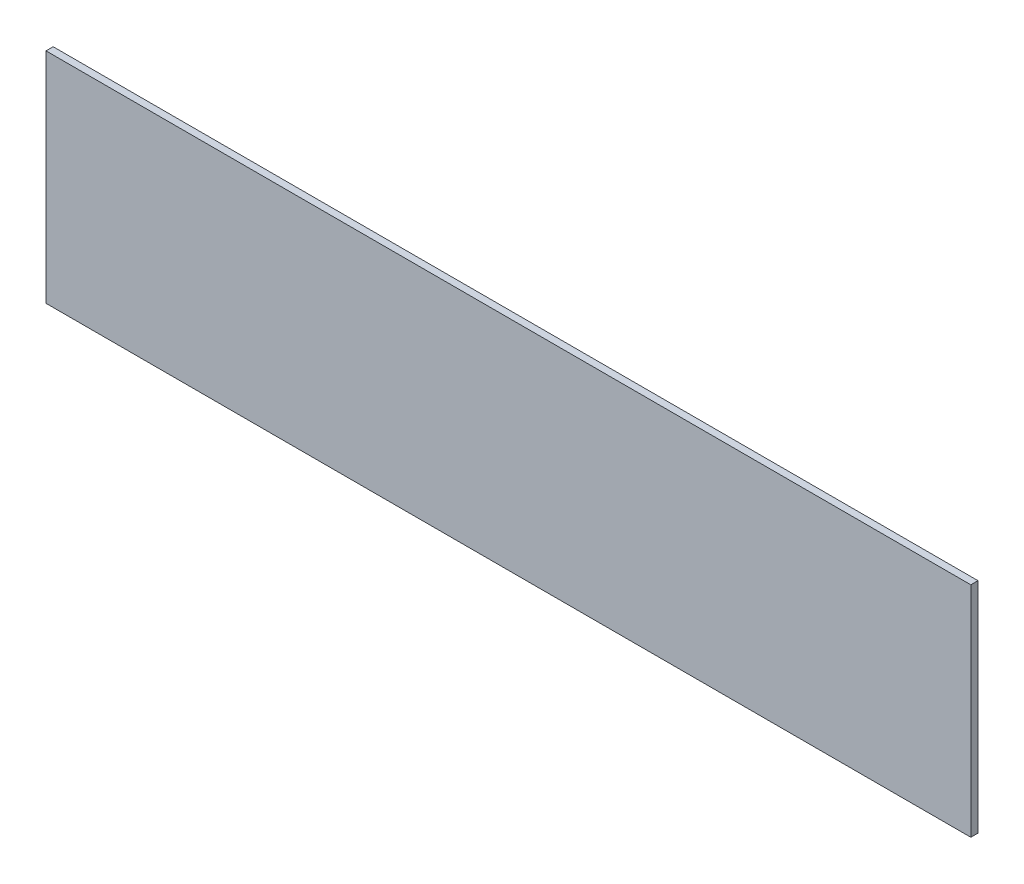
SolidWorks part; units mm, degrees
ref_plane "Front Plane" through (0, 0, 0) normal (0, 0, 1) x (1, 0, 0)
ref_plane "Top Plane" through (0, 0, 0) normal (0, 1, 0) x (1, 0, 0)
ref_plane "Right Plane" through (0, 0, 0) normal (1, 0, 0) x (0, 0, -1)
sketch "Sketch1" plane through (0, 0, 0) normal (0, 0, 1) x (1, 0, 0)
  line L1 (-258, -61) -> (185.4858, -61)
  line L2 (-258, -61) -> (-258, 61)
  line L3 (-258, 61) -> (258, 61)
  line L4 (258, -61) -> (258, 61)
  line L5 (-258, -61) -> (258, 61) construction
  line L6 (-258, 61) -> (258, -61) construction
  line L9 (185.4858, -61) -> (258, -61)
  point P0 (0, 0)
  dimension "D1" = 516
  dimension "D2" = 122
extrude "Boss-Extrude1" add sketch "Sketch1" along normal blind 4
